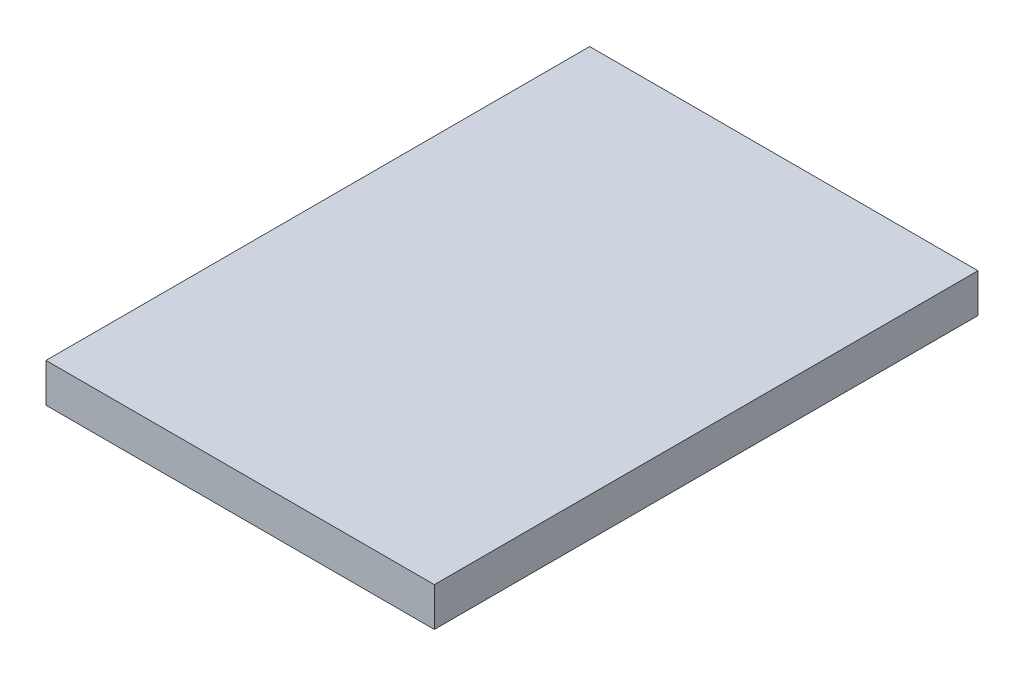
SolidWorks part; units mm, degrees
ref_plane "Front Plane" through (0, 0, 0) normal (0, 0, 1) x (1, 0, 0)
ref_plane "Top Plane" through (0, 0, 0) normal (0, 1, 0) x (1, 0, 0)
ref_plane "Right Plane" through (0, 0, 0) normal (1, 0, 0) x (0, 0, -1)
sketch "Sketch1" plane through (0, 0, 0) normal (0, 1, 0) x (1, 0, 0)
  line L1 (0, 0) -> (-31.75, 0)
  line L2 (0, 0) -> (0, 44.45)
  line L3 (0, 44.45) -> (-31.75, 44.45)
  line L4 (-31.75, 0) -> (-31.75, 44.45)
  dimension "D1" = 44.45
  dimension "D2" = 31.75
extrude "Boss-Extrude1" add sketch "Sketch1" along normal blind 3.175
